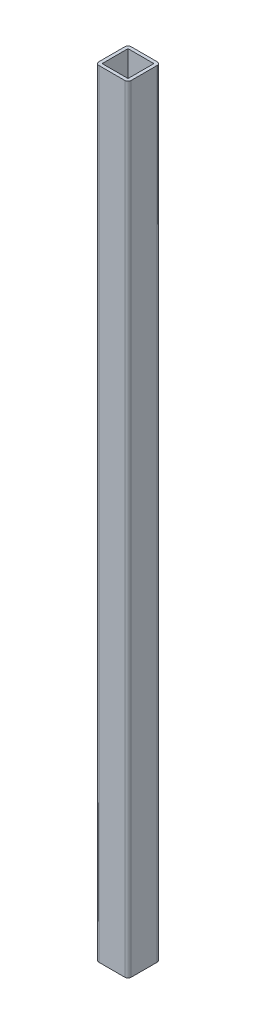
SolidWorks part; units mm, degrees
ref_plane "Front Plane" through (0, 0, 0) normal (0, 0, 1) x (1, 0, 0)
ref_plane "Top Plane" through (0, 0, 0) normal (0, 1, 0) x (1, 0, 0)
ref_plane "Right Plane" through (0, 0, 0) normal (1, 0, 0) x (0, 0, -1)
sketch "Sketch4" plane through (0, 0, 0) normal (0, 1, 0) x (1, 0, 0)
  line L0 (10.16, 10.16) -> (10.16, -10.16)
  line L1 (12.7, 12.7) -> (-12.7, 12.7)
  line L2 (12.7, 12.7) -> (12.7, -12.7)
  line L3 (12.7, -12.7) -> (-12.7, -12.7)
  line L4 (-12.7, 12.7) -> (-12.7, -12.7)
  line L5 (10.16, -10.16) -> (-10.16, -10.16)
  line L6 (-10.16, 10.16) -> (-10.16, -10.16)
  line L7 (10.16, 10.16) -> (-10.16, 10.16)
  point P0 (0, 0)
  dimension "D1" = 25.4
  dimension "D2" = 25.4
  dimension "D3" = 2.54
extrude "Boss-Extrude6" add sketch "Sketch4" along normal blind 609.6 contours L4 L3 L2 L1
shell "Shell1" thickness 2.54
fillet "Fillet1" radius 2.54 4 edges at (-12.7, 304.8, 12.7) (12.7, 304.8, 12.7) (12.7, 304.8, -12.7) (-12.7, 304.8, -12.7)
